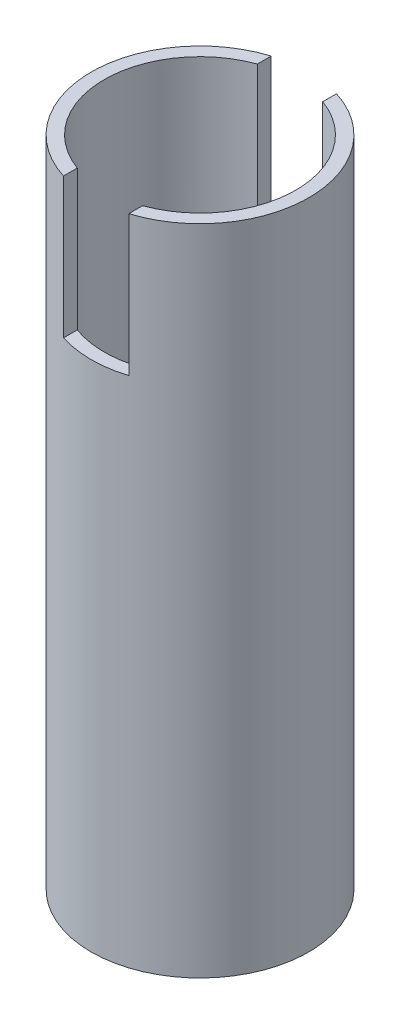
SolidWorks part; units mm, degrees
material "PVC 0.007 Plasticizado"
ref_plane "Plano frontal" through (0, 0, 0) normal (0, 0, 1) x (1, 0, 0)
ref_plane "Plano superior" through (0, 0, 0) normal (0, 1, 0) x (1, 0, 0)
ref_plane "Plano direito" through (0, 0, 0) normal (1, 0, 0) x (0, 0, -1)
sketch "Esboço1" plane through (0, 0, 0) normal (0, 1, 0) x (1, 0, 0)
  circle A0 centre (0, 0) radius 25
  circle A1 centre (0, 0) radius 22
  dimension "D1" = 44
  dimension "D2" = 3
extrude "Ressalto-extrusão1" add sketch "Esboço1" along normal blind 150
sketch "Esboço3" plane through (0, 150, 0) normal (0, 1, 0) x (1, 0, 0)
  line L0 (12.7319, 0) -> (-47.995, 0) construction
  line L1 (0, -27.2162) -> (0, 16.6302) construction
  line L2 (7.5, -20.6821) -> (7.5, -23.8485)
  line L3 (-7.5, -20.6821) -> (-7.5, -23.8485)
  line L4 (-7.5, 23.8485) -> (-7.5, 20.6821)
  line L5 (7.5, 20.6821) -> (7.5, 23.8485)
  arc A0 (7.5, -20.6821) -> (-7.5, -20.6821) centre (0, 0) cw
  circle A1 centre (0, 0) radius 22 construction
  arc A2 (7.5, -23.8485) -> (-7.5, -23.8485) centre (0, 0) cw
  circle A3 centre (0, 0) radius 25 construction
  arc A4 (-7.5, 20.6821) -> (7.5, 20.6821) centre (0, 0) cw
  arc A5 (7.5, 23.8485) -> (-7.5, 23.8485) centre (0, 0) ccw
  dimension "D1" = 15
extrude "Corte-extrusão2" cut sketch "Esboço3" against normal up to surface (32.2 mm away)
